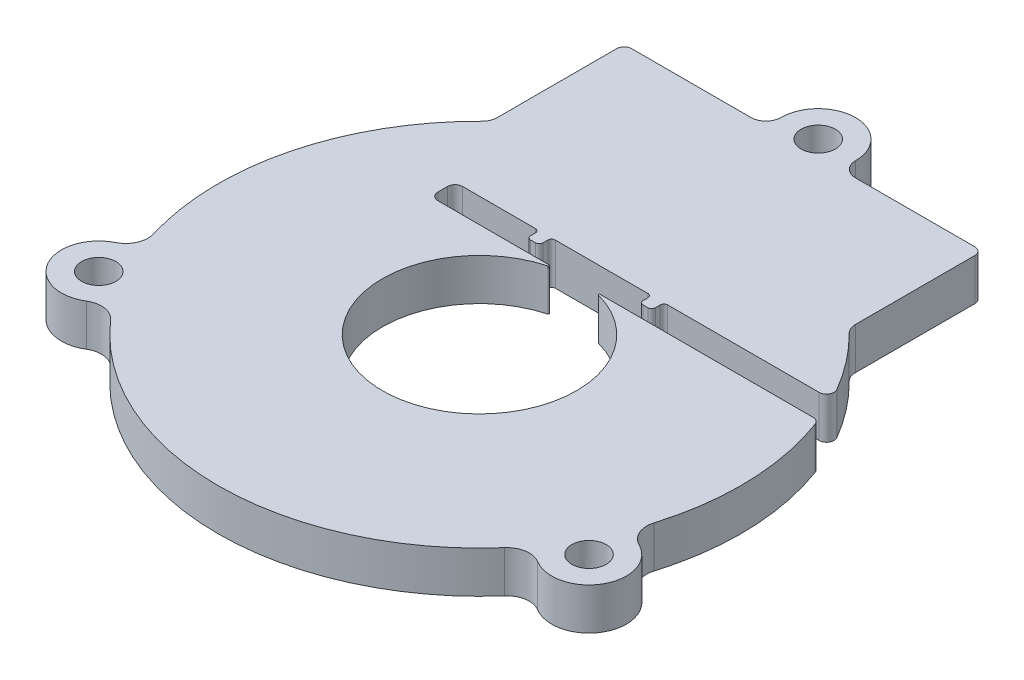
SolidWorks part; units mm, degrees
ref_plane "Front Plane" through (0, 0, 0) normal (0, 0, 1) x (1, 0, 0)
ref_plane "Top Plane" through (0, 0, 0) normal (0, 1, 0) x (1, 0, 0)
ref_plane "Right Plane" through (0, 0, 0) normal (1, 0, 0) x (0, 0, -1)
sketch "Sketch1" plane through (0, 0, 0) normal (0, 1, 0) x (1, 0, 0)
  line L2 (32.785, 0) -> (32.785, 24.2952) construction
  line L7 (32.785, 0) -> (32.785, 18.8) construction
  line L10 (32.785, 66.7015) -> (56.765, 66.7015) construction
  line L11 (32.785, 66.7015) -> (32.785, 59.7015) construction
  line L12 (32.785, 59.7015) -> (56.765, 59.7015) construction
  line L13 (56.765, 66.7015) -> (56.765, 59.7015) construction
  line L15 (56.765, 66.7015) -> (8.805, 66.7015)
  line L16 (56.765, 66.7015) -> (56.765, 41.7015)
  line L17 (56.765, 41.7015) -> (8.805, 41.7015)
  line L18 (8.805, 66.7015) -> (8.805, 41.7015)
  circle A0 centre (32.785, 23.3515) radius 35
  circle A1 centre (65.6, 5.2015) radius 5
  circle A4 centre (-0.03, 5.2015) radius 5
  circle A6 centre (-0.03, 5.2015) radius 2.3
  circle A7 centre (65.6, 5.2015) radius 2.3
  circle A8 centre (32.785, 23.3515) radius 13
  circle A9 centre (32.785, 68.7015) radius 2.3
  circle A10 centre (32.785, 68.7015) radius 5
  point P7 (32.785, 0)
  dimension "D1" = 7
  dimension "D5" = 43.35
  dimension "D7" = 37.5
  dimension "D10" = 4.6
  dimension "D11" = 2
  dimension "D13" = 10
  dimension "D2" = 23.98
  dimension "D3" = 47.96
  dimension "D4" = 25
  dimension "D6" = 37.5
  dimension "D8" = 61.5
  dimension "D9" = 61.5
  dimension "D12" = 0
extrude "Boss-Extrude3" add sketch "Sketch1" along normal blind 5.588 contours A4 | A1 | A0 | L15 L18 L17 L16 | A10 | A6 | A7 | A8
hole_wizard "Ø4.6 (4.6) Diameter Hole1" positions "Sketch4" profile "Sketch5" hole size "Ø4.6" standard "ANSI Metric" end condition through all
sketch "Sketch4" plane through (0, 5.588, 0) normal (0, 1, 0) x (1, 0, 0)
  point P0 (32.785, 68.7015)
sketch "Sketch5" plane through (32.785, 5.588, -68.7015) normal (1, 0, 0) x (0, 0, 1)
  line L0 (0, 0) -> (0, 5.588)
  line L1 (0, 5.588) -> (2.3, 5.588)
  line L2 (2.3, 5.588) -> (2.3, 0)
  line L5 (2.3, 0) -> (0, 0)
  line L11 (0, -6.35) -> (0, 107.95) construction
  dimension "Thru Hole Dia." = 4.6
  dimension "Thru Hole Depth" = 5.588
fillet "Fillet1" radius 3 4 edges at (65.2147, 2.794, -10.1866) (61.1725, 2.794, -2.8783) (4.3975, 2.794, -2.8783) (0.3553, 2.794, -10.1866)
fillet "Fillet2" radius 2 2 edges at (28.2024, 2.794, -66.7015) (37.3676, 2.794, -66.7015)
fillet "Fillet3" radius 2 2 edges at (56.765, 2.794, -48.8458) (8.805, 2.794, -48.8458)
fillet "Fillet4" radius 1 2 edges at (8.805, 2.794, -66.7015) (56.765, 2.794, -66.7015)
sketch "Sketch6" plane through (0, 5.588, 0) normal (0, 1, 0) x (1, 0, 0)
  line L1 (68.5414, 36.1015) -> (13.459, 36.1015)
  line L2 (68.5414, 36.1015) -> (68.5414, 39.4015)
  line L3 (68.5414, 39.4015) -> (13.459, 39.4015)
  line L4 (13.459, 36.1015) -> (13.459, 39.4015)
  circle A0 centre (32.785, 23.3515) radius 13 construction
  dimension "D2" = 12.75
  dimension "D1" = 3.3
extrude "Cut-Extrude5" cut sketch "Sketch6" against normal blind 10
sketch "Sketch7" plane through (0, 5.588, 0) normal (0, 1, 0) x (1, 0, 0)
  line L0 (41.435, 39.4015) -> (39.785, 39.4015)
  line L1 (26.385, 39.4015) -> (24.735, 39.4015)
  line L2 (26.385, 39.4015) -> (26.385, 37.7515)
  line L3 (26.385, 37.7515) -> (24.735, 37.7515)
  line L4 (24.735, 39.4015) -> (24.735, 37.7515)
  line L5 (41.435, 39.4015) -> (41.435, 37.7515)
  line L6 (41.435, 37.7515) -> (39.785, 37.7515)
  line L7 (39.785, 39.4015) -> (39.785, 37.7515)
  arc A1 (30.2478, 36.1015) -> (35.3222, 36.1015) centre (32.785, 23.3515) ccw construction
  dimension "D7" = 7
  dimension "D1" = 1.65
  dimension "D2" = 1.65
  dimension "D3" = 13.4
  dimension "D4" = 16.05
  dimension "D5" = 1.65
  dimension "D6" = 1.65
  dimension "D8" = 16.05
extrude "Boss-Extrude4" add sketch "Sketch7" against normal up to surface (5.588 mm away) up to face at (32.785, 0, -66.4015)
fillet "Fillet5" radius 1 2 edges at (13.459, 2.794, -39.4015) (13.459, 2.794, -36.1015)
fillet "Fillet6" radius 0.5 4 edges at (24.735, 2.794, -39.4015) (26.385, 2.794, -39.4015) (39.785, 2.794, -39.4015) (41.435, 2.794, -39.4015)
fillet "Fillet7" radius 0.5 4 edges at (24.735, 2.794, -37.7515) (26.385, 2.794, -37.7515) (39.785, 2.794, -37.7515) (41.435, 2.794, -37.7515)
fillet "Fillet11" radius 1 2 edges at (63.888, 2.794, -39.4015) (65.3801, 2.794, -36.1015)
fillet "Fillet13" radius 0.1 1 edges at (30.2478, 2.794, -36.1015)
fillet "Fillet14" radius 0.1 1 edges at (35.3222, 2.794, -36.1015)
